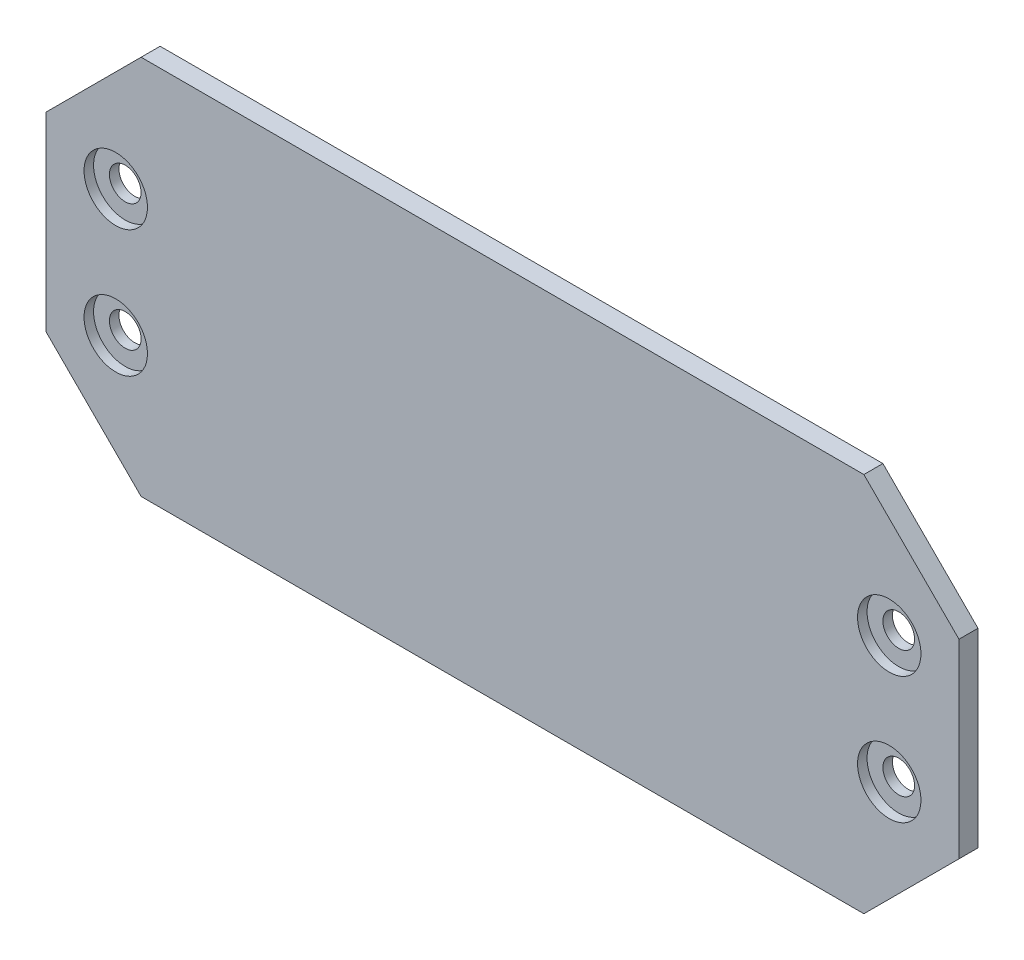
SolidWorks part; units mm, degrees
ref_plane "Front Plane" through (0, 0, 0) normal (0, 0, 1) x (1, 0, 0)
ref_plane "Top Plane" through (0, 0, 0) normal (0, 1, 0) x (1, 0, 0)
ref_plane "Right Plane" through (0, 0, 0) normal (1, 0, 0) x (0, 0, -1)
sketch "Sketch1" plane through (0, 0, 0) normal (0, 0, 1) x (1, 0, 0)
  line L0 (0, -30) -> (0, 30) construction
  line L1 (-57, 30) -> (57, 30)
  line L2 (-72, 15) -> (-72, -15)
  line L3 (-57, -30) -> (57, -30)
  line L4 (72, 15) -> (72, -15)
  line L5 (-72, 0) -> (72, 0) construction
  line L6 (-57, 30) -> (-72, 15)
  line L7 (57, 30) -> (72, 15)
  line L8 (57, -30) -> (72, -15)
  line L9 (-57, -30) -> (-72, -15)
  circle A0 centre (-61, 10) radius 2.5
  circle A1 centre (61, 10) radius 2.5
  circle A2 centre (61, -10) radius 2.5
  circle A3 centre (-61, -10) radius 2.5
  dimension "D3" = 5
  dimension "D1" = 135
  dimension "D2" = 144
  dimension "D4" = 20
  dimension "D5" = 122
  dimension "D6" = 60
  dimension "D7" = 30
extrude "Boss-Extrude1" add sketch "Sketch1" along normal blind 3
sketch "Sketch2" plane through (0, 0, 3) normal (0, 0, 1) x (1, 0, 0)
  circle A0 centre (-61, -10) radius 5
  circle A1 centre (-61, 10) radius 5
  circle A2 centre (61, 10) radius 5
  circle A3 centre (61, -10) radius 5
  dimension "D1" = 10
extrude "Cut-Extrude1" cut sketch "Sketch2" against normal blind 1.5
